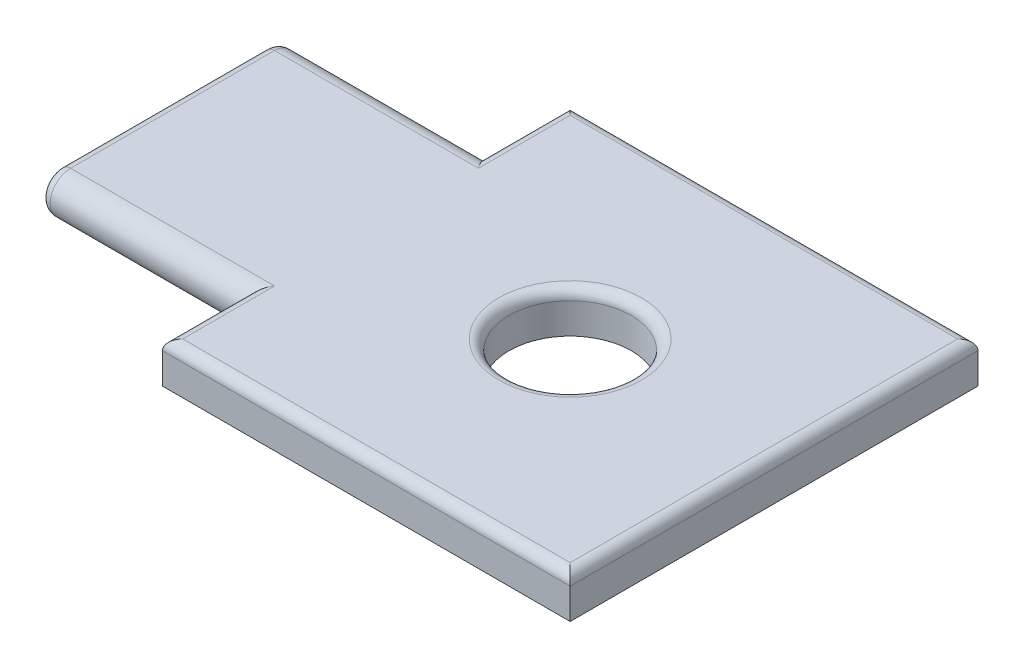
SolidWorks part; units mm, degrees
ref_plane "Front Plane" through (0, 0, 0) normal (0, 0, 1) x (1, 0, 0)
ref_plane "Top Plane" through (0, 0, 0) normal (0, 1, 0) x (1, 0, 0)
ref_plane "Right Plane" through (0, 0, 0) normal (1, 0, 0) x (0, 0, -1)
sketch "Sketch2" plane through (0, 0, 0) normal (0, 1, 0) x (1, 0, 0)
  line L1 (-100, -100) -> (100, -100)
  line L2 (-100, -100) -> (-100, 100)
  line L3 (-100, 100) -> (100, 100)
  line L4 (100, -100) -> (100, 100)
  line L5 (-100, -100) -> (100, 100) construction
  line L6 (-100, 100) -> (100, -100) construction
  circle A0 centre (0, 0) radius 30
extrude "Boss-Extrude2" add sketch "Sketch2" along normal blind 20
sketch "Sketch4" plane through (-100, 0, 0) normal (-1, 0, 0) x (0, 0, 1)
  line L0 (100, 10) -> (-100, 10) construction
  line L1 (100, 20) -> (100, 0) construction
  line L2 (-100, 20) -> (-100, 0) construction
  line L3 (-50, 10) -> (50, 10) construction
  line L4 (-50, 20) -> (50, 20)
  line L5 (-50, 0) -> (50, 0)
  arc A0 (-50, 20) -> (-50, 0) centre (-50, 10) ccw
  arc A1 (50, 0) -> (50, 20) centre (50, 10) ccw
  point P8 (0, 10)
extrude "Boss-Extrude3" add sketch "Sketch4" along normal blind 100
fillet "Fillet1" radius 5 10 edges at (-200, 10, 60) (-200, 0, 0) (-200, 10, -60) (0, 20, 30) (0, 20, 100) (-100, 20, 75) (-200, 20, 0) (-100, 20, -75) (0, 20, -100) (100, 20, 0)
